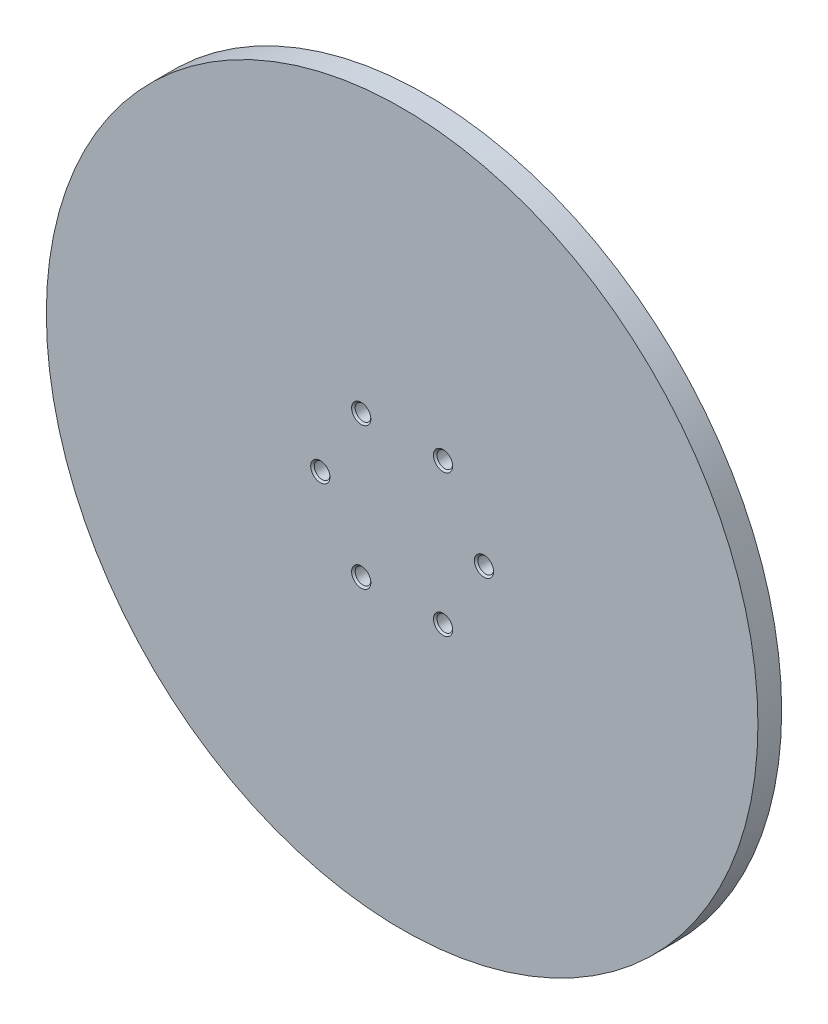
SolidWorks part; units mm, degrees
ref_plane "前视基准面" through (0, 0, 0) normal (0, 0, 1) x (1, 0, 0)
ref_plane "上视基准面" through (0, 0, 0) normal (0, 1, 0) x (1, 0, 0)
ref_plane "右视基准面" through (0, 0, 0) normal (1, 0, 0) x (0, 0, -1)
sketch "草图1" plane through (0, 0, 0) normal (0, 0, 1) x (1, 0, 0)
  circle A0 centre (-61.8332, 36.7016) radius 75
  circle A1 centre (-61.8332, 36.7016) radius 17.25
  dimension "D1" = 150
extrude "凸台-拉伸1" add sketch "草图1" along normal blind 5
sketch "草图2" plane through (0, 0, 5) normal (0, 0, 1) x (1, 0, 0)
  circle A0 centre (-61.8332, 36.7016) radius 17.25
extrude "凸台-拉伸2" add sketch "草图2" against normal blind 5
sketch "草图3" plane through (0, 0, 5) normal (0, 0, 1) x (1, 0, 0)
  point P5 (-79.0832, 36.7016)
hole_wizard "M4 螺纹孔5" positions "草图3" profile "草图4" tap size "M4" standard "GB" end condition through all
sketch "草图4" plane through (-79.0832, 36.7016, 5) normal (1, 0, 0) x (0, -1, 0)
  line L0 (0, 0) -> (0, 5)
  line L1 (0, 5) -> (1.65, 5)
  line L2 (1.65, 5) -> (1.65, 0.375)
  line L3 (1.65, 0.375) -> (2.025, 0)
  line L5 (2.025, 0) -> (0, 0)
  line L6 (-1.65, 0.375) -> (-2.025, 0) construction
  line L11 (0, -6.35) -> (0, 107.95) construction
  dimension "通孔螺纹孔钻头直径" = 3.3
  dimension "通孔螺纹孔钻头深度" = 5
  dimension "近端锥形沉头孔直径" = 4.05
  dimension "近端锥形沉头孔角度" = 90
pattern_circular "阵列(圆周)1" count 6 every 60 about axis through (-61.8332, 36.7016, 0) along (0, 0, 1) of "M4 螺纹孔5"
